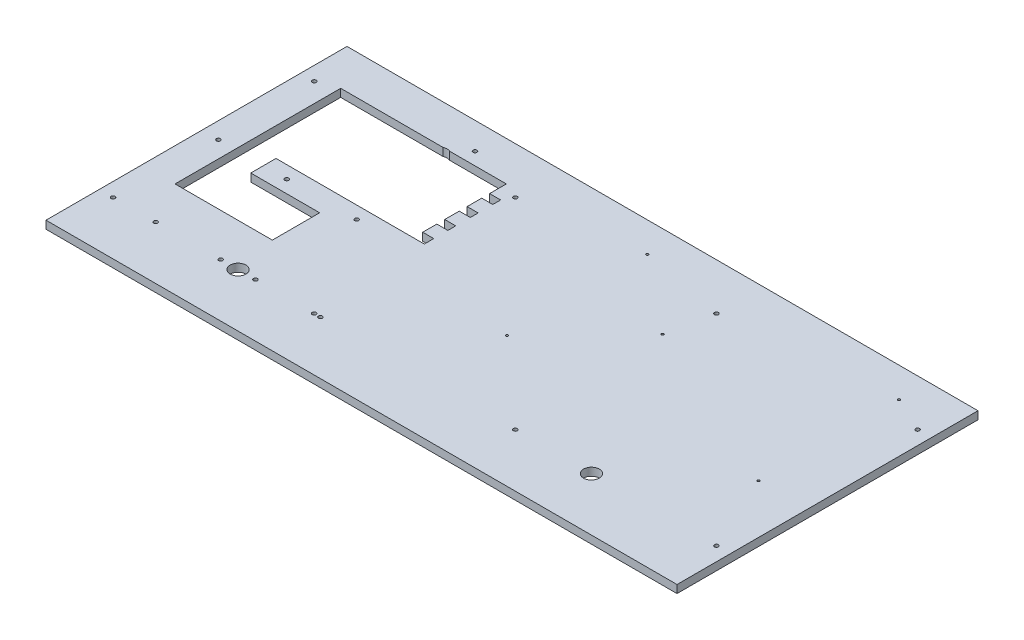
SolidWorks part; units mm, degrees
ref_plane "Front Plane" through (0, 0, 0) normal (0, 0, 1) x (1, 0, 0)
ref_plane "Top Plane" through (0, 0, 0) normal (0, 1, 0) x (1, 0, 0)
ref_plane "Right Plane" through (0, 0, 0) normal (1, 0, 0) x (0, 0, -1)
sketch "Sketch1" plane through (0, 0, 0) normal (0, 1, 0) x (1, 0, 0)
  line L0 (212, 98.3) -> (212, -102.5) construction
  line L1 (-212, -102.5) -> (212, -102.5) construction
  line L2 (-212, -102.5) -> (-212, 98.3) construction
  line L3 (-212, 98.3) -> (212, 98.3) construction
  line L4 (212, 98.3) -> (212, -102.5)
  line L5 (-212, -102.5) -> (212, -102.5)
  line L6 (-212, -102.5) -> (-212, 98.3)
  line L7 (-212, 98.3) -> (212, 98.3)
  circle A1 centre (112, -63.75) radius 4.5 construction
  circle A7 centre (-112, -63.75) radius 4.5 construction
  circle A10 centre (-112, 63.75) radius 4.5 construction
  circle A12 centre (63.75, -63.75) radius 3.5
  circle A13 centre (112, -63.75) radius 4.5
  circle A14 centre (191.25, -63.75) radius 3.5
  circle A15 centre (191.25, 63.75) radius 3.5
  circle A16 centre (112, 63.75) radius 4.5
  circle A17 centre (63.75, 63.75) radius 3.5
  circle A18 centre (-63.75, -63.75) radius 3.5
  circle A19 centre (-112, -63.75) radius 4.5
  circle A20 centre (-191.25, -63.75) radius 3.5
  circle A21 centre (-63.75, 63.75) radius 3.5
  circle A22 centre (-112, 63.75) radius 4.5
  circle A23 centre (-191.25, 63.75) radius 3.5
sketch "Sketch2" plane through (0, 0, 0) normal (0, 1, 0) x (1, 0, 0)
  line L15 (212, 98.3) -> (212, -102.5) construction
  line L16 (-200, 93.3) -> (200, 93.3)
  line L17 (-200, 93.3) -> (-200, -97.5)
  line L18 (-200, -97.5) -> (200, -97.5)
  line L19 (200, 93.3) -> (200, -97.5)
  line L20 (-212, -102.5) -> (-212, 98.3) construction
  line L21 (-212, -102.5) -> (212, -102.5) construction
  line L22 (-212, 98.3) -> (212, 98.3) construction
  dimension "D1" = 12
  dimension "D2" = 12
  dimension "D3" = 5
  dimension "D4" = 5
extrude "Boss-Extrude1" add sketch "Sketch2" along normal blind 5
sketch "Sketch3" plane through (0, 5, 0) normal (0, 1, 0) x (1, 0, 0)
  circle A0 centre (-112, 63.75) radius 5
  circle A2 centre (112, -63.75) radius 5
  circle A3 centre (-112, -63.75) radius 5
  dimension "D1" = 10
extrude "Cut-Extrude1" cut sketch "Sketch3" against normal through all
sketch "Sketch4" plane through (0, 5, 0) normal (0, 1, 0) x (1, 0, 0)
  circle A0 centre (-191.25, 63.75) radius 1.25
  circle A1 centre (-63.75, 63.75) radius 1.25
  circle A2 centre (63.75, 63.75) radius 1.25
  circle A3 centre (191.25, 63.75) radius 1.25
  circle A4 centre (191.25, -63.75) radius 1.25
  circle A5 centre (63.75, -63.75) radius 1.25
  circle A6 centre (-63.75, -63.75) radius 1.25
  circle A7 centre (-191.25, -63.75) radius 1.25
  dimension "D1" = 2.5
extrude "Cut-Extrude2" cut sketch "Sketch4" against normal through all
sketch "Sketch5" plane through (0, 5, 0) normal (0, 1, 0) x (1, 0, 0)
  line L0 (-179, 68.3) -> (-179, -36.7)
  line L1 (-179, -36.7) -> (-117.3272, -36.7)
  line L2 (-117.3272, -36.7) -> (-117.3272, -6.7)
  line L3 (-117.3272, -6.7) -> (-161, -6.7)
  line L4 (-161, -6.7) -> (-161, 9.3)
  line L5 (-161, 9.3) -> (-67, 9.3)
  line L9 (-76.3831, 68.3) -> (-179, 68.3)
  line L10 (-200, 93.3) -> (-200, -97.5) construction
  line L11 (200, 93.3) -> (-200, 93.3) construction
  line L12 (-67, 9.3) -> (-67, 15.3)
  line L13 (-67, 15.3) -> (-74, 15.3)
  line L14 (-74, 15.3) -> (-74, 24.2526)
  line L15 (-74, 24.2526) -> (-67, 24.2526)
  line L16 (-67, 24.2526) -> (-67, 29.2526)
  line L17 (-67, 29.2526) -> (-74, 29.2526)
  line L18 (-74, 29.2526) -> (-74, 38.4512)
  line L19 (-74, 38.4512) -> (-67, 38.4512)
  line L20 (-67, 38.4512) -> (-67, 43.4512)
  line L21 (-67, 43.4512) -> (-74, 43.4512)
  line L22 (-74, 43.4512) -> (-74, 52.7053)
  line L23 (-74, 52.7053) -> (-67, 52.7053)
  line L24 (-67, 52.7053) -> (-67, 57.7053)
  line L25 (-67, 57.7053) -> (-74, 57.7053)
  line L26 (-74, 57.7053) -> (-74, 68.3)
  line L27 (-74, 68.3) -> (-76.3831, 68.3)
  dimension "D1" = 21
  dimension "D2" = 25
  dimension "D3" = 105
  dimension "D4" = 18
  dimension "D5" = 75
  dimension "D6" = 59
  dimension "D7" = 112
  dimension "D8" = 5
  dimension "D9" = 105
  dimension "D10" = 6
extrude "Cut-Extrude3" cut sketch "Sketch5" against normal through all
sketch "Sketch7" plane through (0, 5, 0) normal (0, 1, 0) x (1, 0, 0)
  circle A0 centre (9.4, 74.3) radius 0.75
  circle A1 centre (58.0625, 35.3) radius 0.75
  circle A2 centre (168.9, 74.3) radius 0.75
  circle A3 centre (168.9, -14.7) radius 0.75
  circle A4 centre (9.4, -14.7) radius 0.75
  point P0 (168.9, 74.3)
  point P2 (9.4, 74.3)
  point P4 (58.0625, 35.3)
  point P6 (9.4, -14.7)
  point P8 (168.9, -14.7)
  dimension "D1" = 1.5
extrude "Cut-Extrude4" cut sketch "Sketch7" against normal through all
sketch "Sketch8" plane through (0, 5, 0) normal (0, 1, 0) x (1, 0, 0)
  line L0 (-59.8, -63.75) -> (-164.2, -63.75) construction
  line L1 (-112, -63.75) -> (-112, -52.5861) construction
  circle A0 centre (-164.2, -63.75) radius 1.25
  circle A1 centre (-123, -63.75) radius 1.25
  circle A2 centre (-101, -63.75) radius 1.25
  circle A3 centre (-59.8, -63.75) radius 1.25
  point P3 (-123, -63.75)
  point P4 (-164.2, -63.75)
  point P7 (-101, -63.75)
  point P8 (-59.8, -63.75)
  dimension "D3" = 2.5
  dimension "D1" = 11
  dimension "D2" = 41.2
extrude "Cut-Extrude5" cut sketch "Sketch8" against normal blind 10
sketch "Sketch9" plane through (0, 5, 0) normal (0, 1, 0) x (1, 0, 0)
  line L0 (-189.5, 1.3) -> (-146.2064, 1.3) construction
  line L1 (-101.86, 76.3) -> (-101.86, 1.3) construction
  line L2 (-146.2064, 9.3) -> (-146.2064, -6.7) construction
  line L3 (-161, 9.3) -> (-67, 9.3) construction
  line L4 (-117.3272, -6.7) -> (-161, -6.7) construction
  line L5 (-179, 1.3) -> (-200, 1.3) construction
  line L6 (-179, 68.3) -> (-179, -36.7) construction
  line L7 (-200, 93.3) -> (-200, -97.5) construction
  line L8 (-154.86, 11.593) -> (-70.36, 11.593) construction
  line L9 (-74, 68.3) -> (-109.927, 68.3) construction
  circle A0 centre (-189.5, 1.3) radius 1.25
  circle A1 centre (-146.2064, 1.3) radius 1.25
  circle A2 centre (-101.86, 76.3) radius 1.25
  circle A3 centre (-101.86, 1.3) radius 1.25
  dimension "D2" = 2.5
  dimension "D1" = 8
  dimension "D3" = 53
extrude "Cut-Extrude6" cut sketch "Sketch9" against normal through all
equation "\"D2@Sketch2\"=\"D1@Sketch2\""
